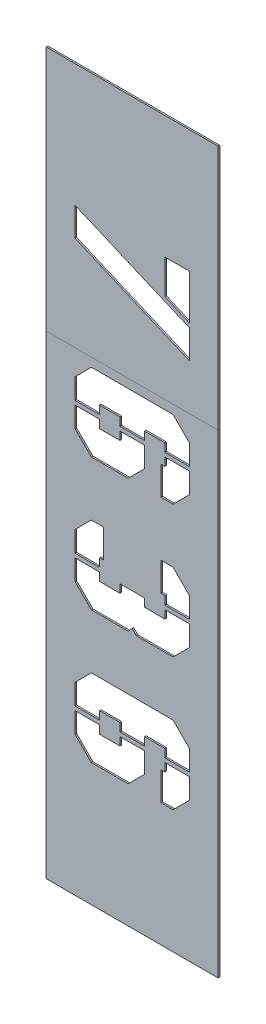
SolidWorks part; units mm, degrees
ref_plane "前基準面" through (0, 0, 0) normal (0, 0, 1) x (1, 0, 0)
ref_plane "上基準面" through (0, 0, 0) normal (0, 1, 0) x (1, 0, 0)
ref_plane "右基準面" through (0, 0, 0) normal (1, 0, 0) x (0, 0, -1)
sketch "草圖1" plane through (0, 0, 0) normal (0, 0, 1) x (1, 0, 0)
  line L1 (-150.4, 629.75) -> (150.4, 629.75)
  line L2 (-150.4, 629.75) -> (-150.4, -629.75)
  line L3 (-150.4, -629.75) -> (150.4, -629.75)
  line L4 (150.4, 629.75) -> (150.4, -629.75)
  line L5 (-150.4, 629.75) -> (150.4, -629.75) construction
  line L6 (-150.4, -629.75) -> (150.4, 629.75) construction
  point P0 (0, 0)
  dimension "D1" = 300.8
  dimension "D2" = 1259.5
extrude "填料-伸長1" add sketch "草圖1" along normal blind 2.75
sketch "草圖2" plane through (0, 0, 2.75) normal (0, 0, 1) x (1, 0, 0)
  line L0 (-150.4, 629.75) -> (-100, 629.75) construction
  line L1 (150.4, 629.75) -> (-150.4, 629.75) construction
  line L2 (-100, 629.75) -> (-100, -629.75) construction
  line L3 (-150.4, -629.75) -> (150.4, -629.75) construction
  text T0 "7636" font "Coburn" height 200
  dimension "D1" = 50.4
extrude "除料-伸長1" cut sketch "草圖2" against normal blind 10
sketch "草圖3" plane through (0, 0, 2.75) normal (0, 0, 1) x (1, 0, 0)
  line L0 (-150.4, 629.75) -> (-150.4, 199.6) construction
  line L1 (-150.4, 629.75) -> (-150.4, -629.75) construction
  line L2 (-150.4, 199.6) -> (150.4, 199.6)
  line L3 (150.4, -629.75) -> (150.4, 629.75) construction
  dimension "D1" = 430.15
split "分割5" trim tools "草圖3" bodies to split 102 resulting bodies 109 110
